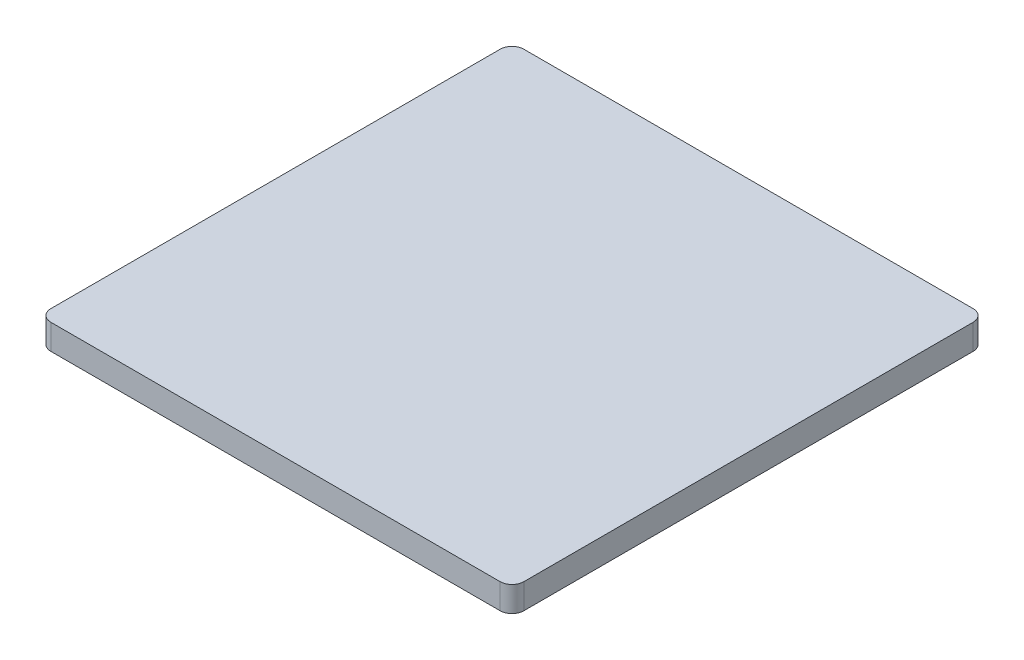
SolidWorks part; units mm, degrees
ref_plane "Piano frontale" through (0, 0, 0) normal (0, 0, 1) x (1, 0, 0)
ref_plane "Piano superiore" through (0, 0, 0) normal (0, 1, 0) x (1, 0, 0)
ref_plane "Piano destro" through (0, 0, 0) normal (1, 0, 0) x (0, 0, -1)
sketch "Schizzo1" plane through (0, 0, 0) normal (0, 1, 0) x (1, 0, 0)
  line L1 (-55.443, -22.0312) -> (-25.443, -22.0312)
  line L2 (-55.443, -22.0312) -> (-55.443, -52.0312)
  line L3 (-55.443, -52.0312) -> (-25.443, -52.0312)
  line L4 (-25.443, -22.0312) -> (-25.443, -52.0312)
  dimension "D1" = 30
  dimension "D2" = 30
extrude "Estrusione-Estrusione1" add sketch "Schizzo1" along normal blind 1.6
fillet "Raccordo1" radius 0.75 4 edges at (-55.443, 0.8, 22.0312) (-25.443, 0.8, 22.0312) (-55.443, 0.8, 52.0312) (-25.443, 0.8, 52.0312)
